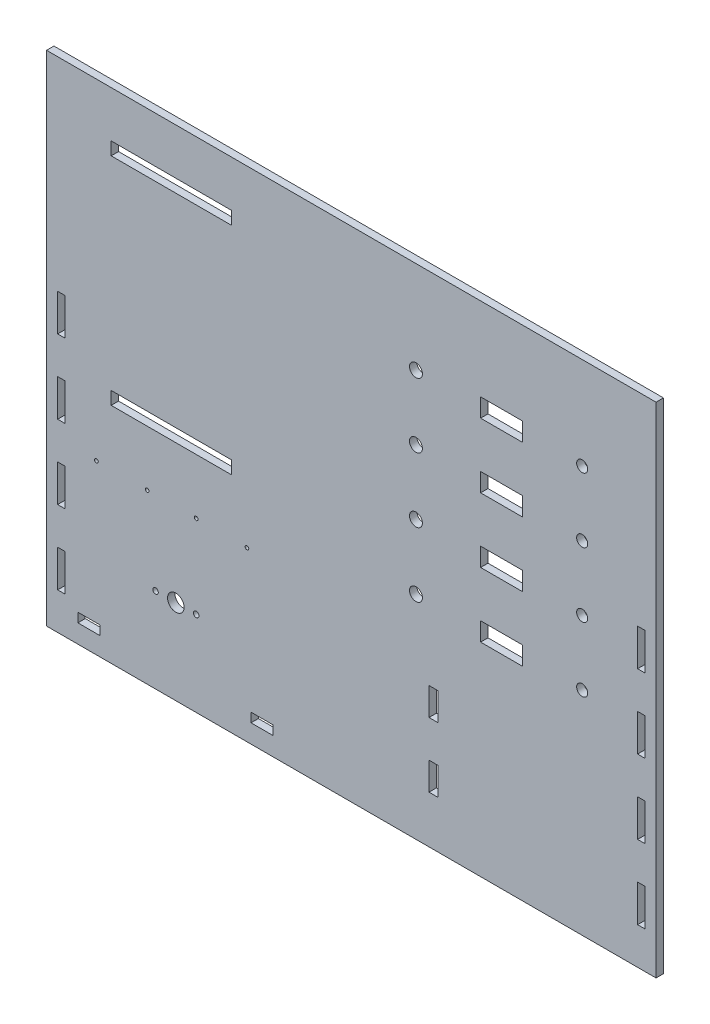
SolidWorks part; units mm, degrees
ref_plane "Piano frontale" through (0, 0, 0) normal (0, 0, 1) x (1, 0, 0)
ref_plane "Piano superiore" through (0, 0, 0) normal (0, 1, 0) x (1, 0, 0)
ref_plane "Piano destro" through (0, 0, 0) normal (1, 0, 0) x (0, 0, -1)
sketch "Schizzo1" plane through (0, 0, 0) normal (0, 0, 1) x (1, 0, 0)
  line L0 (235, 180) -> (235, 190)
  line L1 (0, 0) -> (330, 0)
  line L2 (0, 0) -> (0, 270)
  line L3 (0, 270) -> (330, 270)
  line L4 (330, 0) -> (330, 270)
  line L13 (35, 245) -> (100, 245)
  line L14 (35, 245) -> (35, 238)
  line L15 (35, 238) -> (100, 238)
  line L16 (100, 245) -> (100, 238)
  line L17 (235, 215) -> (257.7, 215)
  line L18 (235, 215) -> (235, 225)
  line L19 (235, 225) -> (257.7, 225)
  line L20 (257.7, 215) -> (257.7, 225)
  line L21 (235, 180) -> (257.7, 180)
  line L22 (257.7, 180) -> (257.7, 190)
  line L23 (235, 190) -> (257.7, 190)
  line L24 (235, 145) -> (235, 155)
  line L25 (235, 145) -> (257.7, 145)
  line L26 (257.7, 145) -> (257.7, 155)
  line L27 (235, 155) -> (257.7, 155)
  line L28 (235, 110) -> (235, 120)
  line L29 (235, 110) -> (257.7, 110)
  line L30 (257.7, 110) -> (257.7, 120)
  line L31 (235, 120) -> (257.7, 120)
  line L32 (6, 120) -> (6, 100)
  line L37 (35, 128) -> (100, 128)
  line L38 (35, 128) -> (35, 121)
  line L39 (35, 121) -> (100, 121)
  line L40 (100, 128) -> (100, 121)
  line L41 (207.0633, 60.6779) -> (212.0633, 60.6779)
  line L42 (16.9471, 10) -> (28.9471, 10)
  line L43 (16.9471, 10) -> (16.9471, 15)
  line L44 (16.9471, 15) -> (28.9471, 15)
  line L45 (28.9471, 10) -> (28.9471, 15)
  line L46 (110.6872, 10) -> (122.6872, 10)
  line L47 (110.6872, 10) -> (110.6872, 15)
  line L48 (110.6872, 15) -> (122.6872, 15)
  line L49 (122.6872, 10) -> (122.6872, 15)
  line L50 (207.0633, 60.6779) -> (207.0633, 75.6779)
  line L51 (207.0633, 75.6779) -> (212.0633, 75.6779)
  line L52 (212.0633, 60.6779) -> (212.0633, 75.6779)
  line L53 (207.0633, 40.6779) -> (212.0633, 40.6779)
  line L54 (207.0633, 40.6779) -> (207.0633, 25.6779)
  line L55 (207.0633, 25.6779) -> (212.0633, 25.6779)
  line L56 (212.0633, 40.6779) -> (212.0633, 25.6779)
  line L57 (6, 160) -> (10, 160)
  line L58 (6, 160) -> (6, 140)
  line L59 (6, 140) -> (10, 140)
  line L60 (10, 160) -> (10, 140)
  line L61 (6, 120) -> (10, 120)
  line L62 (10, 120) -> (10, 100)
  line L63 (6, 100) -> (10, 100)
  line L64 (6, 80) -> (6, 60)
  line L65 (6, 80) -> (10, 80)
  line L66 (10, 80) -> (10, 60)
  line L67 (6, 60) -> (10, 60)
  line L68 (6, 40) -> (6, 20)
  line L69 (6, 40) -> (10, 40)
  line L70 (10, 40) -> (10, 20)
  line L71 (6, 20) -> (10, 20)
  line L72 (320, 120) -> (320, 100)
  line L73 (320, 160) -> (324, 160)
  line L74 (320, 160) -> (320, 140)
  line L75 (320, 140) -> (324, 140)
  line L76 (324, 160) -> (324, 140)
  line L77 (320, 120) -> (324, 120)
  line L78 (324, 120) -> (324, 100)
  line L79 (320, 100) -> (324, 100)
  line L80 (320, 80) -> (320, 60)
  line L81 (320, 80) -> (324, 80)
  line L82 (324, 80) -> (324, 60)
  line L83 (320, 60) -> (324, 60)
  line L84 (320, 40) -> (320, 20)
  line L85 (320, 40) -> (324, 40)
  line L86 (324, 40) -> (324, 20)
  line L87 (320, 20) -> (324, 20)
  circle A4 centre (200, 220) radius 3.5
  circle A5 centre (200, 185) radius 3.5
  circle A6 centre (200, 150) radius 3.5
  circle A7 centre (200, 115) radius 3.5
  circle A8 centre (27, 91) radius 1
  circle A9 centre (54.5, 91) radius 1
  circle A10 centre (81, 91) radius 1
  circle A11 centre (108.5, 91) radius 1
  circle A12 centre (290, 220) radius 3
  circle A13 centre (290, 185) radius 3
  circle A14 centre (290, 150) radius 3
  circle A15 centre (290, 115) radius 3
  circle A16 centre (70, 46) radius 4.5
  circle A17 centre (59, 46) radius 1.5
  circle A18 centre (81, 46) radius 1.5
  point P73 (209.5633, 40.6779)
  point P108 (0, 0)
  point P109 (0, 0)
  point P110 (62.2046, 38.2391)
  dimension "D3" = 25
  dimension "D5" = 7
  dimension "D15" = 7
  dimension "D17" = 35
  dimension "D22" = 2
  dimension "D23" = 2
  dimension "D7" = 30
  dimension "D8" = 27
  dimension "D35" = 90
  dimension "D36" = 6
  dimension "D10" = 9
  dimension "D19" = 3
  dimension "D20" = 3
  dimension "D31" = 46
  dimension "D52" = 70
  dimension "D53" = 22
  dimension "D1" = 270
  dimension "D2" = 330
  dimension "D6" = 110
  dimension "D9" = 26.5
  dimension "D11" = 65
  dimension "D12" = 7
  dimension "D13" = 22.7
  dimension "D14" = 10
  dimension "D16" = 5
  dimension "D4" = 35
  dimension "D25" = 11
  dimension "D26" = 12
  dimension "D27" = 5
  dimension "D28" = 5
  dimension "D29" = 12
  dimension "D30" = 11
  dimension "D32" = 10
  dimension "D33" = 50
  dimension "D34" = 200
  dimension "D38" = 5
  dimension "D39" = 35
  dimension "D40" = 15
  dimension "D41" = 15
  dimension "D42" = 4
  dimension "D43" = 20
  dimension "D44" = 160
  dimension "D45" = 4
  dimension "D46" = 6
  dimension "D47" = 4
  dimension "D48" = 6
  dimension "D49" = 20
  dimension "D50" = 160
  dimension "D18" = 4
  dimension "D21" = 2
  dimension "D24" = 2
  dimension "D37" = 4
  dimension "D51" = 4
extrude "Estrusione-Estrusione1" add sketch "Schizzo1" along normal blind 4
sketch "Schizzo2" plane through (0, 0, 4) normal (0, 0, 1) x (1, 0, 0)
  line L0 (183, 234.3) -> (303, 234.3)
  line L1 (183, 232.5) -> (303, 232.5)
  line L2 (178, 227.5) -> (178, 212.5)
  line L3 (183, 207.5) -> (303, 207.5)
  line L4 (308, 227.5) -> (308, 212.5)
  line L5 (140.6148, 215.5) -> (169.535, 215.5)
  line L6 (212, 220.75) -> (227, 220.75)
  line L12 (212, 220.75) -> (212, 219.25)
  line L13 (212, 219.25) -> (227, 219.25)
  line L14 (227, 219.25) -> (227, 217.75)
  line L15 (227, 217.75) -> (232, 220)
  line L16 (232, 220) -> (227, 222.25)
  line L17 (227, 222.25) -> (227, 220.75)
  line L18 (235, 225) -> (235, 215) construction
  line L19 (183, 199.3) -> (303, 199.3)
  line L20 (183, 197.5) -> (303, 197.5)
  line L21 (178, 192.5) -> (178, 177.5)
  line L22 (183, 172.5) -> (303, 172.5)
  line L23 (308, 192.5) -> (308, 177.5)
  line L24 (212, 185.75) -> (227, 185.75)
  line L25 (212, 185.75) -> (212, 184.25)
  line L26 (212, 184.25) -> (227, 184.25)
  line L27 (227, 184.25) -> (227, 182.75)
  line L28 (227, 182.75) -> (232, 185)
  line L29 (232, 185) -> (227, 187.25)
  line L30 (227, 187.25) -> (227, 185.75)
  line L31 (140.6148, 180.5) -> (169.535, 180.5)
  line L32 (183, 164.3) -> (303, 164.3)
  line L33 (183, 162.5) -> (303, 162.5)
  line L34 (178, 157.5) -> (178, 142.5)
  line L35 (183, 137.5) -> (303, 137.5)
  line L36 (308, 157.5) -> (308, 142.5)
  line L37 (212, 150.75) -> (227, 150.75)
  line L38 (212, 150.75) -> (212, 149.25)
  line L39 (212, 149.25) -> (227, 149.25)
  line L40 (227, 149.25) -> (227, 147.75)
  line L41 (227, 147.75) -> (232, 150)
  line L42 (232, 150) -> (227, 152.25)
  line L43 (227, 152.25) -> (227, 150.75)
  line L44 (140.6148, 145.5) -> (169.535, 145.5)
  line L45 (183, 129.3) -> (303, 129.3)
  line L46 (183, 127.5) -> (303, 127.5)
  line L47 (178, 122.5) -> (178, 107.5)
  line L48 (183, 102.5) -> (303, 102.5)
  line L49 (308, 122.5) -> (308, 107.5)
  line L50 (212, 115.75) -> (227, 115.75)
  line L51 (212, 115.75) -> (212, 114.25)
  line L52 (212, 114.25) -> (227, 114.25)
  line L53 (227, 114.25) -> (227, 112.75)
  line L54 (227, 112.75) -> (232, 115)
  line L55 (232, 115) -> (227, 117.25)
  line L56 (227, 117.25) -> (227, 115.75)
  line L57 (140.6148, 110.5) -> (169.535, 110.5)
  circle A0 centre (200, 220) radius 3.5 construction
  arc A1 (308, 227.5) -> (303, 232.5) centre (303, 227.5) ccw
  arc A2 (308, 212.5) -> (303, 207.5) centre (303, 212.5) cw
  arc A3 (183, 207.5) -> (178, 212.5) centre (183, 212.5) cw
  arc A4 (183, 232.5) -> (178, 227.5) centre (183, 227.5) ccw
  arc A5 (308, 192.5) -> (303, 197.5) centre (303, 192.5) ccw
  arc A6 (308, 177.5) -> (303, 172.5) centre (303, 177.5) cw
  arc A7 (183, 172.5) -> (178, 177.5) centre (183, 177.5) cw
  arc A8 (183, 197.5) -> (178, 192.5) centre (183, 192.5) ccw
  arc A9 (308, 157.5) -> (303, 162.5) centre (303, 157.5) ccw
  arc A10 (308, 142.5) -> (303, 137.5) centre (303, 142.5) cw
  arc A11 (183, 137.5) -> (178, 142.5) centre (183, 142.5) cw
  arc A12 (183, 162.5) -> (178, 157.5) centre (183, 157.5) ccw
  arc A13 (308, 122.5) -> (303, 127.5) centre (303, 122.5) ccw
  arc A14 (308, 107.5) -> (303, 102.5) centre (303, 107.5) cw
  arc A15 (183, 102.5) -> (178, 107.5) centre (183, 107.5) cw
  arc A16 (183, 127.5) -> (178, 122.5) centre (183, 122.5) ccw
  text T0 "   Analog           Value [V]         Digital" font "Ebrima" height 5
  text T1 "Input 1" font "Ebrima" height 7
  text T2 "   Analog           Value [V]         Digital\r\n" font "Ebrima" height 5
  text T3 "Input 2" font "Ebrima" height 7
  text T4 "   Analog           Value [V]         Digital\r\n" font "Ebrima" height 5
  text T5 "Input 3" font "Ebrima" height 7
  text T6 "   Analog           Value [V]         Digital\r\n" font "Ebrima" height 5
  text T7 "Input 4" font "Ebrima" height 7
  point P11 (308, 232.5)
  point P18 (178, 207.5)
  point P21 (178, 232.5)
  point P31 (212, 220)
  point P34 (235, 220)
  dimension "D4" = 12.5
  dimension "D6" = 5
  dimension "D1" = 25
  dimension "D2" = 130
  dimension "D3" = 22
  dimension "D5" = 1.8
  dimension "D7" = 15
  dimension "D8" = 1.5
  dimension "D9" = 1.5
  dimension "D10" = 1.5
  dimension "D11" = 5
  dimension "D12" = 3
  dimension "D13" = 8
  dimension "D14" = 4
sketch "Schizzo4" plane through (0, 0, 4) normal (0, 0, 1) x (1, 0, 0)
  line L0 (298, 223.5) -> (303, 223.5)
  line L1 (298, 211.5) -> (303, 211.5)
  line L2 (183, 207.5) -> (303, 207.5) construction
  line L3 (308, 227.5) -> (308, 212.5) construction
  line L4 (298, 188.5) -> (303, 188.5) construction
  line L5 (298, 176.5) -> (303, 176.5) construction
  line L6 (298, 188.5) -> (303, 188.5)
  line L7 (298, 176.5) -> (303, 176.5)
  line L8 (298, 153.5) -> (303, 153.5) construction
  line L9 (298, 141.5) -> (303, 141.5) construction
  line L10 (298, 153.5) -> (303, 153.5)
  line L11 (298, 141.5) -> (303, 141.5)
  line L12 (298, 118.5) -> (303, 118.5) construction
  line L13 (298, 106.5) -> (303, 106.5) construction
  line L14 (298, 118.5) -> (303, 118.5)
  line L15 (298, 106.5) -> (303, 106.5)
  text T0 "1" font "Ebrima" height 5
  text T1 "0" font "Ebrima" height 5
  text T2 "1" font "Ebrima" height 5
  text T3 "0" font "Ebrima" height 5
  text T4 "1" font "Ebrima" height 5
  text T5 "0" font "Ebrima" height 5
  text T6 "1" font "Ebrima" height 5
  text T7 "0" font "Ebrima" height 5
  dimension "D1" = 12
  dimension "D2" = 4
  dimension "D3" = 5
  dimension "D4" = 5
  dimension "D5" = 4
sketch "Schizzo5" plane through (0, 0, 4) normal (0, 0, 1) x (1, 0, 0)
  line L0 (31.9112, 99.8388) -> (49.5888, 82.1612)
  line L1 (49.5888, 99.8388) -> (31.9112, 82.1612)
  line L2 (85.9112, 99.8388) -> (103.5888, 82.1612)
  line L3 (103.5888, 99.8388) -> (85.9112, 82.1612)
  circle A0 centre (40.75, 91) radius 12.5
  circle A1 centre (94.75, 91) radius 12.5
  dimension "D2" = 25
  dimension "D1" = 13.75
  dimension "D3" = 2
sketch "Schizzo6" plane through (0, 0, 4) normal (0, 0, 1) x (1, 0, 0)
  line L0 (27, 106) -> (110.7261, 106)
  text T0 "Output 1             Output 2" font "Ebrima" height 5
  dimension "D1" = 15
sketch "Schizzo7" plane through (0, 0, 4) normal (0, 0, 1) x (1, 0, 0)
  line L0 (183, 102.5) -> (303, 102.5) construction
  line L5 (203, 80.5) -> (283, 80.5)
  line L6 (198, 75.5) -> (198, 60.5)
  line L7 (203, 55.5) -> (283, 55.5)
  line L8 (288, 75.5) -> (288, 60.5)
  line L9 (156.3076, 63.5) -> (188.8793, 63.5)
  line L10 (156.3076, 28.064) -> (188.8793, 28.064) construction
  line L11 (178, 122.5) -> (178, 107.5) construction
  line L12 (308, 122.5) -> (308, 107.5) construction
  line L13 (203, 82.3) -> (283, 82.3)
  line L14 (156.3076, 28.064) -> (188.8793, 28.064)
  line L15 (203, 20.064) -> (283, 20.064)
  line L16 (198, 40.064) -> (198, 25.064)
  line L17 (203, 45.064) -> (283, 45.064)
  line L18 (288, 40.064) -> (288, 25.064)
  line L19 (203, 46.864) -> (283, 46.864)
  line L20 (203, 47.3) -> (283, 47.3) construction
  line L30 (203, 46.864) -> (283, 46.864) construction
  line L31 (156.3076, 28.064) -> (188.8793, 28.064) construction
  arc A0 (288, 60.5) -> (283, 55.5) centre (283, 60.5) cw
  arc A1 (283, 80.5) -> (288, 75.5) centre (283, 75.5) cw
  arc A2 (203, 80.5) -> (198, 75.5) centre (203, 75.5) ccw
  arc A3 (203, 55.5) -> (198, 60.5) centre (203, 60.5) cw
  arc A4 (203, 20.064) -> (198, 25.064) centre (203, 25.064) cw
  arc A5 (203, 45.064) -> (198, 40.064) centre (203, 40.064) ccw
  arc A6 (283, 45.064) -> (288, 40.064) centre (283, 40.064) cw
  arc A7 (288, 25.064) -> (283, 20.064) centre (283, 25.064) cw
  text T0 "Input 5" font "Ebrima" height 7
  text T1 "Temperature Sensor" font "Ebrima" height 5
  text T2 "Input 6" font "Ebrima" height 7
  text T3 "Temperature Sensor" font "Ebrima" height 5
  text T4 "Input 5" font "Ebrima" height 7
  text T5 "Light Sensor" font "Ebrima" height 5
  point P19 (198, 80.5)
  point P22 (198, 55.5)
  dimension "D4" = 5
  dimension "D3" = 25
  dimension "D5" = 20
  dimension "D6" = 20
  dimension "D7" = 1.8
  dimension "D8" = 22
  dimension "D9" = 8
  dimension "D10" = 2
sketch "Schizzo8" plane through (0, 0, 4) normal (0, 0, 1) x (1, 0, 0)
  line L0 (11.8588, 54.2415) -> (33.9689, 54.2415)
  line L1 (104.234, 54.2415) -> (126.4133, 54.2415)
  line L2 (42.3218, 57.4396) -> (47.8676, 55.1496)
  line L3 (40, 46) -> (46, 46)
  line L4 (48.8338, 67.1271) -> (53.0859, 62.8939)
  line L5 (58.5502, 73.5959) -> (60.8648, 68.0603)
  line L6 (70, 75.8668) -> (70.0267, 69.8669)
  line L7 (81.4498, 73.5959) -> (79.1845, 68.04)
  line L8 (91.1662, 67.1271) -> (86.9519, 62.8562)
  line L9 (97.6782, 57.4396) -> (92.153, 55.1004)
  line L10 (100, 46) -> (94.0002, 45.9466)
  line L13 (40, 30.0398) -> (68, 30.0398)
  line L14 (40, 13.3361) -> (68, 13.3361)
  line L15 (72, 30.0398) -> (100, 30.0398)
  line L16 (72, 13.3361) -> (100, 13.3361)
  arc A0 (40, 46) -> (100, 46) centre (70, 46) cw
  text T0 "Input 7" font "Ebrima" height 5
  text T1 "Input 8" font "Ebrima" height 5
  text T2 "Output 3" font "Ebrima" height 5
  text T3 "↻" font "Ebrima" height 15
  text T4 "↺" font "Ebrima" height 15
  text T5 "Output 4" font "Ebrima" height 5
  point P33 (70, 45.8665)
  dimension "D2" = 30
  dimension "D1" = 6
  dimension "D4" = 28
  dimension "D5" = 28
  dimension "D6" = 2
  dimension "D7" = 4
  dimension "D3" = 9
sketch "Schizzo10" plane through (0, 0, 4) normal (0, 0, 1) x (1, 0, 0)
  line L0 (0, 255.9385) -> (330.0757, 255.9385)
  text T0 "Arduino OPTA Control Board" font "Ebrima" height 10
